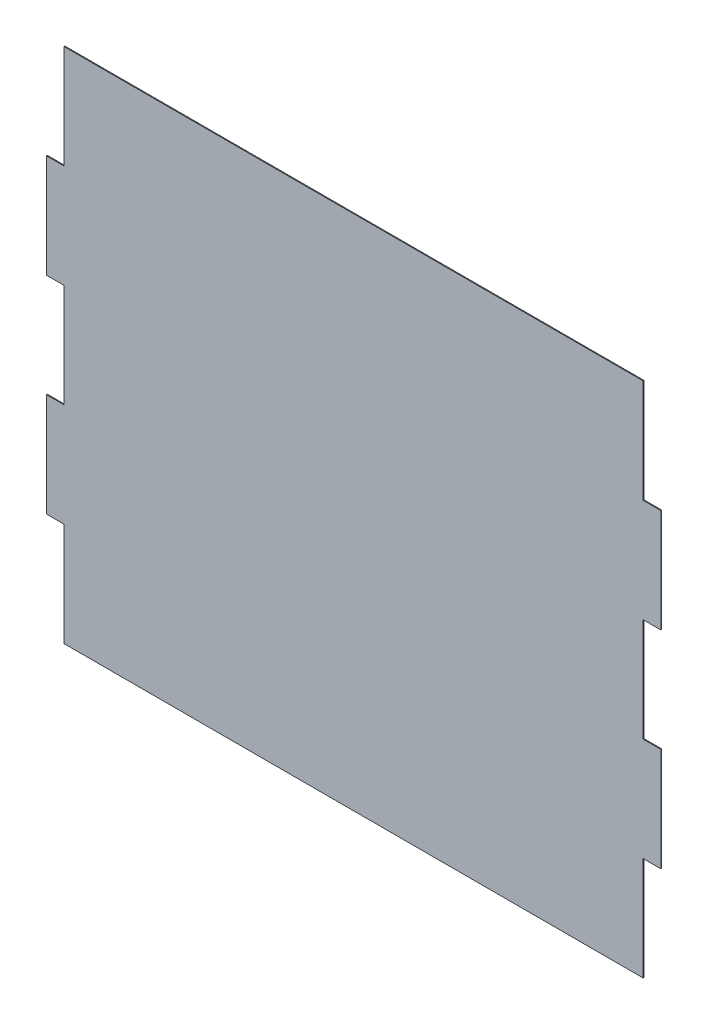
SolidWorks part; units mm, degrees
ref_plane "Front Plane" through (0, 0, 0) normal (0, 0, 1) x (1, 0, 0)
ref_plane "Top Plane" through (0, 0, 0) normal (0, 1, 0) x (1, 0, 0)
ref_plane "Right Plane" through (0, 0, 0) normal (1, 0, 0) x (0, 0, -1)
sketch "Sketch1" plane through (0, 0, 0) normal (0, 0, 1) x (1, 0, 0)
  line L0 (-84, 45) -> (-89.1239, 45)
  line L1 (84, 45) -> (84, 75)
  line L2 (89.1239, 15) -> (84, 15)
  line L3 (84, 75) -> (-84, 75)
  line L4 (-84, -15) -> (-84, 15)
  line L5 (89.1239, 45) -> (89.1239, 15)
  line L6 (84, -15) -> (84, 15)
  line L7 (-89.1239, 45) -> (-89.1239, 15)
  line L8 (-89.1239, 15) -> (-84, 15)
  line L9 (-84, 45) -> (-84, 75)
  line L10 (0, 55.7393) -> (0, -57.202) construction
  line L11 (0, 0) -> (-110.5718, 0) construction
  line L12 (84, 45) -> (89.1239, 45)
  line L13 (84, -45) -> (89.1239, -45)
  line L14 (-84, -45) -> (-84, -75)
  line L15 (-89.1239, -15) -> (-84, -15)
  line L16 (-89.1239, -45) -> (-89.1239, -15)
  line L17 (89.1239, -45) -> (89.1239, -15)
  line L18 (84, -75) -> (-84, -75)
  line L19 (89.1239, -15) -> (84, -15)
  line L20 (84, -45) -> (84, -75)
  line L21 (-84, -45) -> (-89.1239, -45)
  point P0 (0, 0)
  point P19 (0, 75)
  point P27 (84, 0)
  point P28 (-84, 0)
  point P29 (0, -75)
  dimension "D1" = 84
  dimension "D2" = 75
  dimension "D3" = 30
  dimension "D4" = 30
extrude "Boss-Extrude1" add sketch "Sketch1" along normal mid plane 0.25 contours L3 L9 L0 L7 L8 L4 L15 L16 L21 L14 L18 L20 L13 L17 L19 L6 L2 L5 L12 L1
